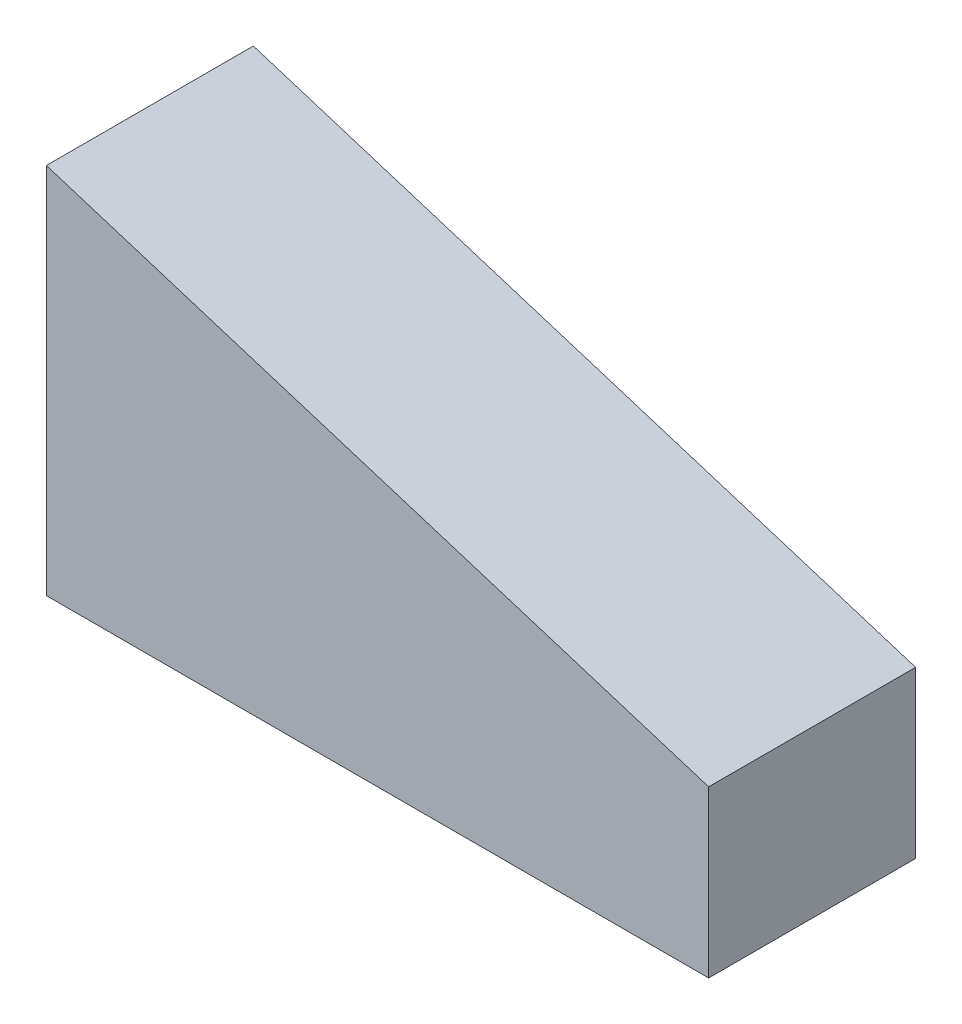
SolidWorks part; units mm, degrees
ref_plane "Front Plane" through (0, 0, 0) normal (0, 0, 1) x (1, 0, 0)
ref_plane "Top Plane" through (0, 0, 0) normal (0, 1, 0) x (1, 0, 0)
ref_plane "Right Plane" through (0, 0, 0) normal (1, 0, 0) x (0, 0, -1)
sketch "Sketch1" plane through (0, 0, 0) normal (0, 0, 1) x (1, 0, 0)
  line L0 (0, 0) -> (0, 45)
  line L1 (0, 45) -> (80, 20)
  line L2 (80, 20) -> (80, 0)
  line L3 (80, 0) -> (0, 0)
  dimension "D1" = 45
  dimension "D2" = 80
  dimension "D3" = 20
extrude "Boss-Extrude1" add sketch "Sketch1" along normal blind 25
